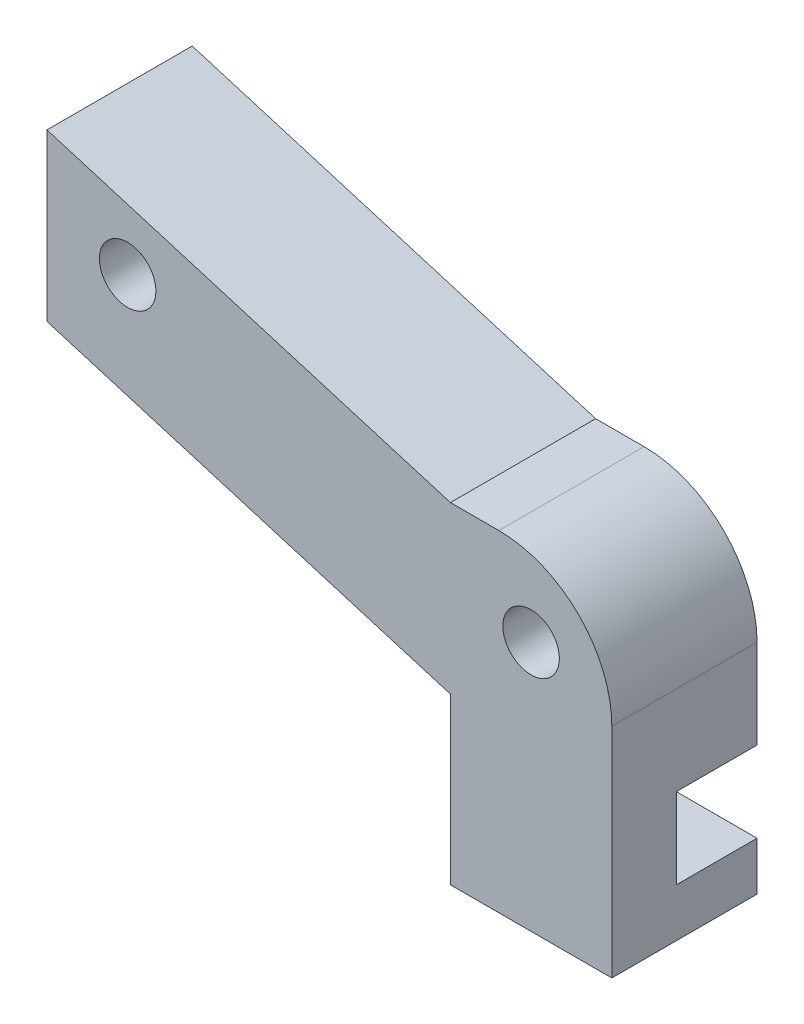
SolidWorks part; units mm, degrees
ref_plane "Front Plane" through (0, 0, 0) normal (0, 0, 1) x (1, 0, 0)
ref_plane "Top Plane" through (0, 0, 0) normal (0, 1, 0) x (1, 0, 0)
ref_plane "Right Plane" through (0, 0, 0) normal (1, 0, 0) x (0, 0, -1)
sketch "Sketch2" plane through (0, 0, 0) normal (0, 0, 1) x (1, 0, 0)
  line L0 (-15.8158, -97.1932) -> (-15.8158, -107.4744)
  line L1 (-15.8158, -97.1932) -> (9.1842, -104.6932)
  line L2 (-15.8158, -107.4744) -> (9.1842, -114.9744)
  line L8 (9.1842, -104.6932) -> (19.1842, -104.6932)
  line L9 (19.1842, -114.9744) -> (19.1842, -104.6932)
  line L12 (19.1842, -114.9744) -> (19.1842, -125.2065)
  line L13 (19.1842, -125.2065) -> (9.1842, -125.2065)
  line L14 (9.1842, -114.9744) -> (9.1842, -125.2065)
  dimension "D1" = 10
extrude "Boss-Extrude1" add sketch "Sketch2" along normal blind 9
sketch "Sketch3" plane through (0, 0, 9) normal (0, 0, 1) x (1, 0, 0)
  line L3 (19.1842, -125.2065) -> (19.1842, -104.6932) construction
  line L4 (-15.8158, -107.4744) -> (19.1842, -107.4744) construction
  circle A0 centre (14.1842, -109.6932) radius 1.75
  circle A1 centre (-10.8158, -102.4744) radius 1.75
extrude "Cut-Extrude1" cut sketch "Sketch3" against normal blind 9
sketch "Sketch5" plane through (0, -125.2065, 0) normal (0, -1, 0) x (1, 0, 0)
  line L0 (9.1842, 9) -> (9.1842, 0) construction
  line L2 (9.1842, 9) -> (19.1842, 9) construction
  circle A0 centre (14.1842, 3) radius 1.5
  dimension "D1" = 5
  dimension "D2" = 6
extrude "Cut-Extrude2" cut sketch "Sketch5" against normal blind 10 contours A0
sketch "Sketch6" plane through (19.1842, 0, 0) normal (1, 0, 0) x (0, 0, -1)
  line L6 (0, -125.2065) -> (0, -104.6932) construction
  line L7 (-9, -125.2065) -> (0, -125.2065) construction
  line L8 (0, -122.2065) -> (-5, -122.2065)
  line L9 (0, -122.2065) -> (0, -117.2065)
  line L10 (0, -117.2065) -> (-5, -117.2065)
  line L11 (-5, -122.2065) -> (-5, -117.2065)
  dimension "D1" = 3
  dimension "D2" = 5
  dimension "D3" = 5
extrude "Cut-Extrude3" cut sketch "Sketch6" against normal blind 10
fillet "Fillet1" radius 7 1 edges at (19.1842, -104.6932, 4.5)
